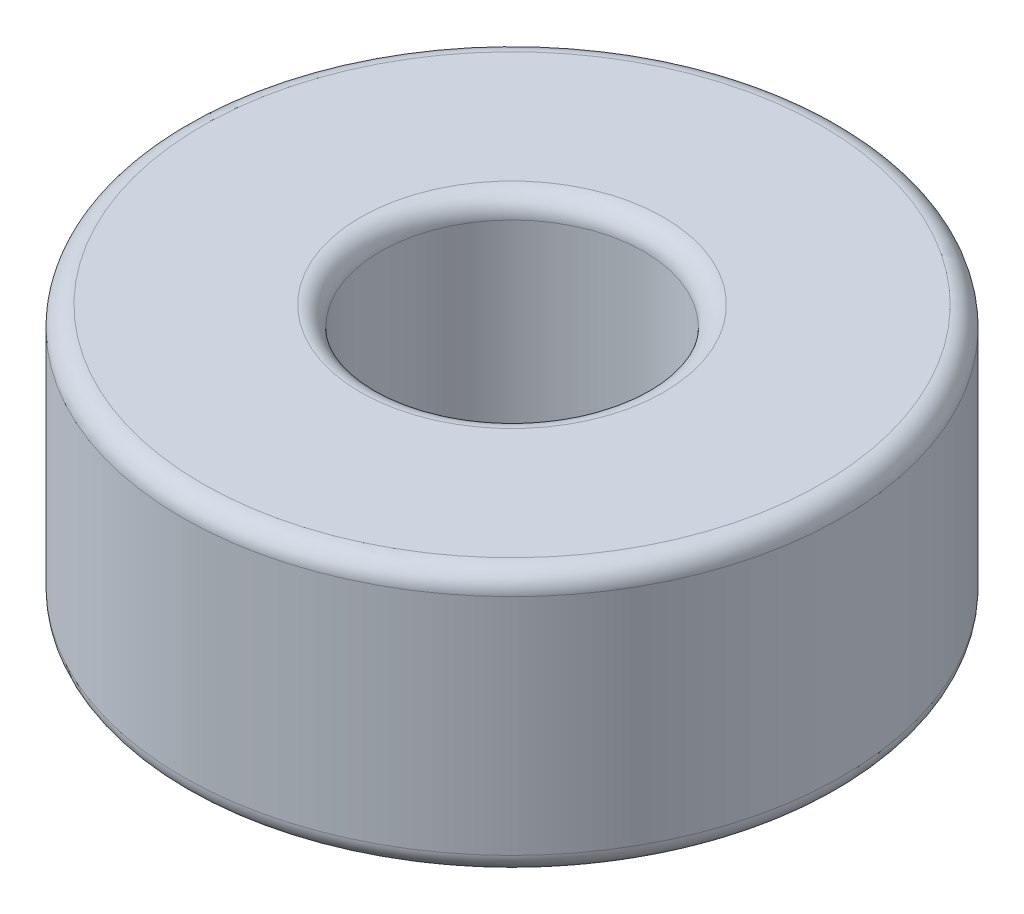
SolidWorks part; units mm, degrees
ref_plane "Front Plane" through (0, 0, 0) normal (0, 0, 1) x (1, 0, 0)
ref_plane "Top Plane" through (0, 0, 0) normal (0, 1, 0) x (1, 0, 0)
ref_plane "Right Plane" through (0, 0, 0) normal (1, 0, 0) x (0, 0, -1)
sketch "Sketch1" plane through (0, 0, 0) normal (0, 1, 0) x (1, 0, 0)
  circle A0 centre (-50.3384, 5.6792) radius 2
  circle A1 centre (-50.3384, 5.6792) radius 5
extrude "Boss-Extrude1" add sketch "Sketch1" along normal blind 4
fillet "Fillet1" radius 0.3 4 edges at (-50.3384, 0, -3.6792) (-50.3384, 4, -3.6792) (-50.3384, 0, -0.6792) (-50.3384, 4, -0.6792)
